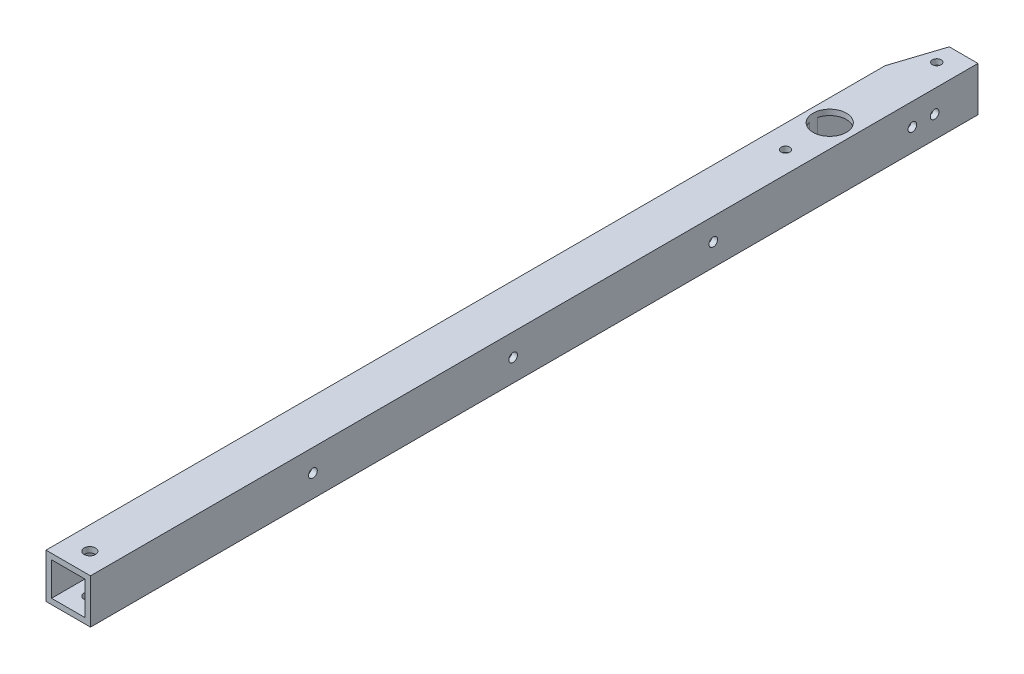
SolidWorks part; units mm, degrees
material "6061 Alloy"
ref_plane "Front Plane" through (0, 0, 0) normal (0, 0, 1) x (1, 0, 0)
ref_plane "Top Plane" through (0, 0, 0) normal (0, 1, 0) x (1, 0, 0)
ref_plane "Right Plane" through (0, 0, 0) normal (1, 0, 0) x (0, 0, -1)
sketch "Sketch1" plane through (0, 0, 0) normal (0, 0, 1) x (1, 0, 0)
  line L0 (-9.525, 9.525) -> (9.525, 9.525)
  line L2 (-12.7, 12.7) -> (12.7, 12.7)
  line L3 (-12.7, 12.7) -> (-12.7, -12.7)
  line L4 (-12.7, -12.7) -> (12.7, -12.7)
  line L5 (12.7, 12.7) -> (12.7, -12.7)
  line L10 (9.525, 9.525) -> (9.525, -9.525)
  line L11 (-9.525, -9.525) -> (9.525, -9.525)
  line L12 (-9.525, 9.525) -> (-9.525, -9.525)
  point P12 (0, 12.7)
  point P14 (12.7, 0)
  dimension "Wall Thickness" = 3.175
  dimension "Outside Width" = 25.4
  dimension "Outside Height" = 25.4
  dimension "Inside Height" = 19.05
  dimension "Inside Width" = 19.05
sketch "Sketch2" plane through (0, 0, 0) normal (1, 0, 0) x (0, 0, -1)
  line L0 (260.35, 0) -> (-260.35, 0)
  point P4 (0, 0)
  point P7 (-260.35, 0)
  point P10 (260.35, 0)
  dimension "Length" = 520.7
sketch "Sketch3" plane through (0, 0, 0) normal (0, 0, 1) x (1, 0, 0)
  line L21 (12.7, 12.7) -> (-12.7, 12.7)
  line L22 (12.7, -12.7) -> (12.7, 12.7)
  line L23 (-12.7, -12.7) -> (12.7, -12.7)
  line L24 (-12.7, 12.7) -> (-12.7, -12.7)
  line L25 (12.7, 12.7) -> (-12.7, 12.7)
  line L26 (12.7, -12.7) -> (12.7, 12.7)
  line L27 (-12.7, -12.7) -> (12.7, -12.7)
  line L28 (-12.7, 12.7) -> (-12.7, -12.7)
  line L29 (9.525, 9.525) -> (-9.525, 9.525)
  line L30 (9.525, -9.525) -> (9.525, 9.525)
  line L31 (-9.525, -9.525) -> (9.525, -9.525)
  line L32 (-9.525, 9.525) -> (-9.525, -9.525)
  line L33 (9.525, 9.525) -> (-9.525, 9.525)
  line L34 (9.525, -9.525) -> (9.525, 9.525)
  line L35 (-9.525, -9.525) -> (9.525, -9.525)
  line L36 (-9.525, 9.525) -> (-9.525, -9.525)
  dimension "D1" = 0
  dimension "D2" = 0
extrude "Boss-Extrude1" add sketch "Sketch3" along normal up to vertex (260.35 mm away) and the other way up to vertex (260.35 mm away) up to point (0, 0, 260.35) other way up to point (0, 0, -260.35)
sketch "Drawing Reference" plane through (0, 0, 0) normal (1, 0, 0) x (0, 0, -1)
  line L0 (-260.35, 0) -> (260.35, 0) construction
  line L1 (0, -12.7) -> (0, 12.7) construction
  line L2 (-260.35, -12.7) -> (260.35, -12.7) construction
  line L5 (-260.35, 12.7) -> (260.35, 12.7) construction
  point P7 (-242.062, 0)
  point P8 (242.062, 0)
  dimension "D1" = 18.288
sketch "Sketch4" plane through (0, 12.7, 0) normal (0, 1, 0) x (1, 0, 0)
  line L7 (-12.7, 218.6635) -> (-12.7, 260.35)
  line L10 (-12.7, -260.35) -> (-12.7, 260.35) construction
  line L11 (-12.7, 260.35) -> (12.7, 260.35)
  line L12 (12.7, 260.35) -> (12.7, 246.38)
  line L13 (12.7, -260.35) -> (12.7, 260.35) construction
  line L14 (12.7, 246.38) -> (-3.6932, 246.38)
  line L15 (-3.6932, 246.38) -> (-12.7, 218.6635)
  dimension "D1" = 13.97
  dimension "D2" = 41.6865
  dimension "D3" = 9.0068
extrude "Cut-Extrude1" cut sketch "Sketch4" against normal blind 25.4
sketch "Sketch5" plane through (0, 12.7, 0) normal (0, -1, 0) x (1, 0, 0)
  circle A0 centre (-0.2787, -174.7012) radius 9.525
extrude "Cut-Extrude2" cut sketch "Sketch5" along normal through all
sketch "Sketch6" plane through (12.7, 0, 0) normal (1, 0, 0) x (0, 0, -1)
  line L0 (246.38, 0) -> (208.915, 0) construction
  line L1 (246.38, -12.7) -> (246.38, 12.7) construction
  line L2 (208.915, 0) -> (227.965, 0) construction
  dimension "D1" = 37.465
hole_wizard "#10 Clearance Hole2" positions "Sketch9" profile "Sketch10" hole size "#10" standard "ANSI Inch" end condition through all
sketch "Sketch9" plane through (0, -12.7, 0) normal (0, -1, 0) x (-1, 0, 0)
  point P0 (-0.379, 148.7845)
  point P3 (-0.3824, 235.171)
sketch "Sketch10" plane through (0.379, -12.7, -148.7845) normal (1, 0, 0) x (0, 0, -1)
  line L0 (0, 0) -> (0, 25.4)
  line L1 (0, 25.4) -> (2.4892, 25.4)
  line L2 (2.4892, 25.4) -> (2.4892, 0)
  line L5 (2.4892, 0) -> (0, 0)
  line L11 (0, -6.35) -> (0, 107.95) construction
  dimension "Thru Hole Dia." = 4.9784
  dimension "Thru Hole Depth" = 25.4
sketch "Sketch15" plane through (0, -12.7, 0) normal (0, -1, 0) x (1, 0, 0)
  line L0 (0.3633, 248.3836) -> (0.3633, 260.35) construction
  line L1 (-12.7, 260.35) -> (12.7, 260.35) construction
  circle A0 centre (0.3633, 248.3836) radius 3.175 construction
  point P2 (0, 260.35)
  dimension "D1" = 11.9664
  dimension "D2" = 0.3633
hole_wizard "1/4 Clearance Hole1" positions "Sketch11" profile "Sketch12" hole size "1/4" standard "ANSI Inch" end condition through all
sketch "Sketch11" plane through (0, -12.7, 0) normal (0, -1, 0) x (-1, 0, 0)
  point P0 (-0.3633, -248.3836)
sketch "Sketch12" plane through (0.3633, -12.7, 248.3836) normal (1, 0, 0) x (0, 0, -1)
  line L0 (0, 0) -> (0, 25.4)
  line L1 (0, 25.4) -> (3.2639, 25.4)
  line L2 (3.2639, 25.4) -> (3.2639, 0)
  line L5 (3.2639, 0) -> (0, 0)
  line L11 (0, -6.35) -> (0, 107.95) construction
  dimension "Thru Hole Dia." = 6.5278
  dimension "Thru Hole Depth" = 25.4
hole_wizard "#10 Clearance Hole3" positions "Sketch13" profile "Sketch14" hole size "#10" standard "ANSI Inch"
sketch "Sketch13" plane through (12.7, 0, 0) normal (1, 0, 0) x (0, 0, -1)
  point P0 (221.6129, -0.0596)
  point P4 (208.915, 0)
sketch "Sketch14" plane through (12.7, -0.0596, -221.6129) normal (0, 1, 0) x (0, 0, -1)
  line L0 (0, 0) -> (0, 6.5757)
  line L1 (0, 6.5757) -> (2.4892, 5.08)
  line L2 (2.4892, 5.08) -> (2.4892, 0)
  line L5 (2.4892, 0) -> (0, 0)
  line L10 (0, 6.5757) -> (-2.4892, 5.08) construction
  line L11 (0, -6.35) -> (0, 107.95) construction
  dimension "Hole Dia." = 4.9784
  dimension "Hole Depth" = 5.08
  dimension "Drill Angle" = 118
sketch "Sketch16" plane through (12.7, 0, 0) normal (1, 0, 0) x (0, 0, -1)
  line L0 (-260.35, 0) -> (-133.35, 0) construction
  line L1 (-260.35, -12.7) -> (-260.35, 12.7) construction
  line L2 (-133.35, 0) -> (-19.05, 0) construction
  line L3 (-19.05, 0) -> (95.25, 0) construction
  dimension "D1" = 127
  dimension "D2" = 114.3
  dimension "D3" = 114.3
hole_wizard "#10 Clearance Hole4" positions "Sketch17" profile "Sketch18" hole size "#10" standard "ANSI Inch" end condition through all
sketch "Sketch17" plane through (12.7, 0, 0) normal (1, 0, 0) x (0, 0, -1)
  point P0 (-133.35, 0)
  point P3 (-19.05, 0)
  point P6 (95.25, 0)
sketch "Sketch18" plane through (12.7, 0, 133.35) normal (0, 1, 0) x (0, 0, -1)
  line L0 (0, 0) -> (0, 25.4)
  line L1 (0, 25.4) -> (2.4892, 25.4)
  line L2 (2.4892, 25.4) -> (2.4892, 0)
  line L5 (2.4892, 0) -> (0, 0)
  line L11 (0, -6.35) -> (0, 107.95) construction
  dimension "Thru Hole Dia." = 4.9784
  dimension "Thru Hole Depth" = 25.4
sketch "Sketch19" plane through (-12.7, 0, 0) normal (-1, 0, 0) x (0, 0, 1)
  line L0 (260.35, 0) -> (228.6, 0) construction
  line L1 (260.35, 12.7) -> (260.35, -12.7) construction
  line L2 (228.6, 0) -> (101.6, 0) construction
  dimension "D1" = 31.75
  dimension "D2" = 127
hole_wizard "1/4 (0.25) Diameter Hole1" positions "Sketch20" profile "Sketch21" hole size "1/4" standard "ANSI Inch"
sketch "Sketch20" plane through (-12.7, 0, 0) normal (-1, 0, 0) x (0, 0, 1)
  point P0 (101.6, 0)
  point P3 (228.6, 0)
sketch "Sketch21" plane through (-12.7, 0, 101.6) normal (0, 1, 0) x (0, 0, 1)
  line L0 (0, 0) -> (0, 6.9877)
  line L1 (0, 6.9877) -> (3.175, 5.08)
  line L2 (3.175, 5.08) -> (3.175, 0)
  line L5 (3.175, 0) -> (0, 0)
  line L10 (0, 6.9877) -> (-3.175, 5.08) construction
  line L11 (0, -6.35) -> (0, 107.95) construction
  dimension "Hole Dia." = 6.35
  dimension "Hole Depth" = 5.08
  dimension "Drill Angle" = 118
equation "\"D1@Drawing Reference\"=\"Outside Width@Sketch1\" * 0.72"
